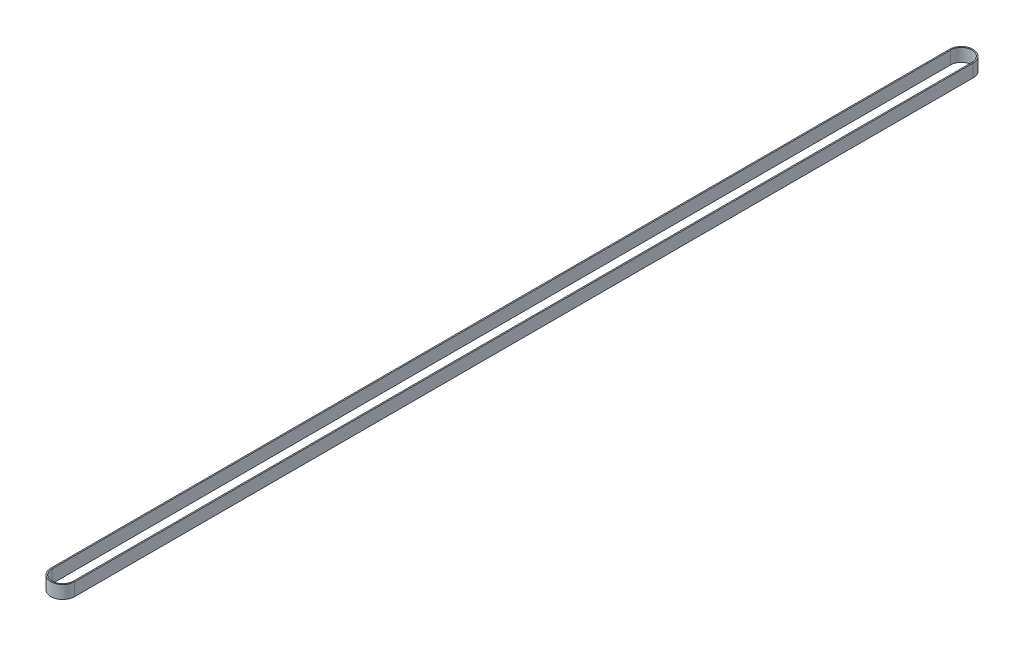
SolidWorks part; units mm, degrees
ref_plane "Front Plane" through (0, 0, 0) normal (0, 0, 1) x (1, 0, 0)
ref_plane "Top Plane" through (0, 0, 0) normal (0, 1, 0) x (1, 0, 0)
ref_plane "Right Plane" through (0, 0, 0) normal (1, 0, 0) x (0, 0, -1)
sketch "Sketch1" plane through (0, 0, 0) normal (0, 1, 0) x (1, 0, 0)
  line L0 (-9.05, 400) -> (-9.05, -362.5)
  line L1 (9.05, -362.5) -> (9.05, 400)
  line L2 (-10.05, 400) -> (-10.05, -362.5)
  line L3 (10.05, -362.5) -> (10.05, 400)
  arc A0 (-9.05, -362.5) -> (9.05, -362.5) centre (0, -362.5) ccw
  arc A1 (9.05, 400) -> (-9.05, 400) centre (0, 400) ccw
  arc A2 (-10.05, -362.5) -> (10.05, -362.5) centre (0, -362.5) ccw
  arc A3 (10.05, 400) -> (-10.05, 400) centre (0, 400) ccw
  dimension "D2" = 20.1
  dimension "D3" = 762.5
  dimension "D1" = 1
extrude "Boss-Extrude1" add sketch "Sketch1" along normal blind 11
